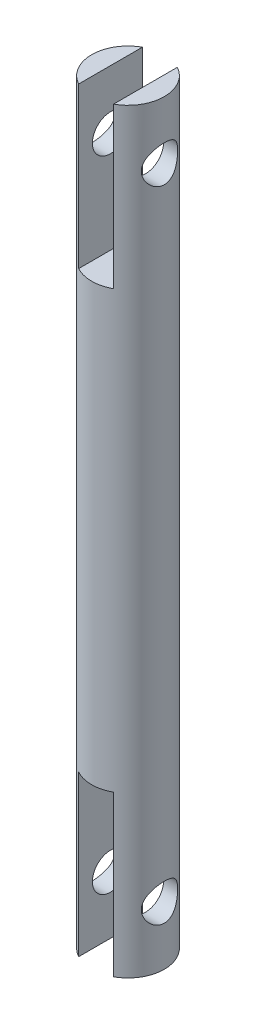
SolidWorks part; units mm, degrees
ref_plane "Front Plane" through (0, 0, 0) normal (1, 0, 0) x (0, 1, 0)
ref_plane "Top Plane" through (0, 0, 0) normal (0, 0, 1) x (0, 1, 0)
ref_plane "Right Plane" through (0, 0, 0) normal (0, 1, 0) x (-1, 0, 0)
sketch "Sketch2" plane through (0, 0, 0) normal (0, 1, 0) x (-1, 0, 0)
  circle A0 centre (0, 0) radius 2.5
  dimension "D1" = 5
extrude "Boss-Extrude1" add sketch "Sketch2" along normal blind 52 contours A0
sketch "Sketch3" plane through (0, 0, 0) normal (0, -1, 0) x (1, 0, 0)
  line L1 (-1.2, -2.5) -> (1.2, -2.5)
  line L2 (-1.2, -2.5) -> (-1.2, 2.5)
  line L3 (-1.2, 2.5) -> (1.2, 2.5)
  line L4 (1.2, -2.5) -> (1.2, 2.5)
  line L5 (-1.2, -2.5) -> (1.2, 2.5) construction
  line L6 (-1.2, 2.5) -> (1.2, -2.5) construction
  circle A0 centre (0, 0) radius 2.5 construction
  point P0 (0, 0)
  dimension "D1" = 2.4
extrude "Cut-Extrude1" cut sketch "Sketch3" against normal blind 11 contours L2 L3 L4 L1
sketch "Sketch4" plane through (0, 0, 0) normal (1, 0, 0) x (0, 1, 0)
  line L0 (0, 0) -> (52, 0) construction
  line L1 (52, -2.5) -> (52, 2.5) construction
  line L2 (0, 2.1932) -> (0, -2.1932) construction
  circle A0 centre (4, 0) radius 1.25
  circle A1 centre (48, 0) radius 1.25
  dimension "D2" = 2.5
  dimension "D1" = 44
  dimension "D3" = 4
extrude "Cut-Extrude2" cut sketch "Sketch4" against normal through all and the other way through all
sketch "Sketch5" plane through (0, 52, 0) normal (0, 1, 0) x (-1, 0, 0)
  line L1 (-1.2, -2.5) -> (1.2, -2.5)
  line L2 (-1.2, -2.5) -> (-1.2, 2.5)
  line L3 (-1.2, 2.5) -> (1.2, 2.5)
  line L4 (1.2, -2.5) -> (1.2, 2.5)
  line L5 (-1.2, -2.5) -> (1.2, 2.5) construction
  line L6 (-1.2, 2.5) -> (1.2, -2.5) construction
  circle A0 centre (0, 0) radius 2.5 construction
  point P0 (0, 0)
  dimension "D1" = 2.4
extrude "Cut-Extrude3" cut sketch "Sketch5" against normal blind 11
